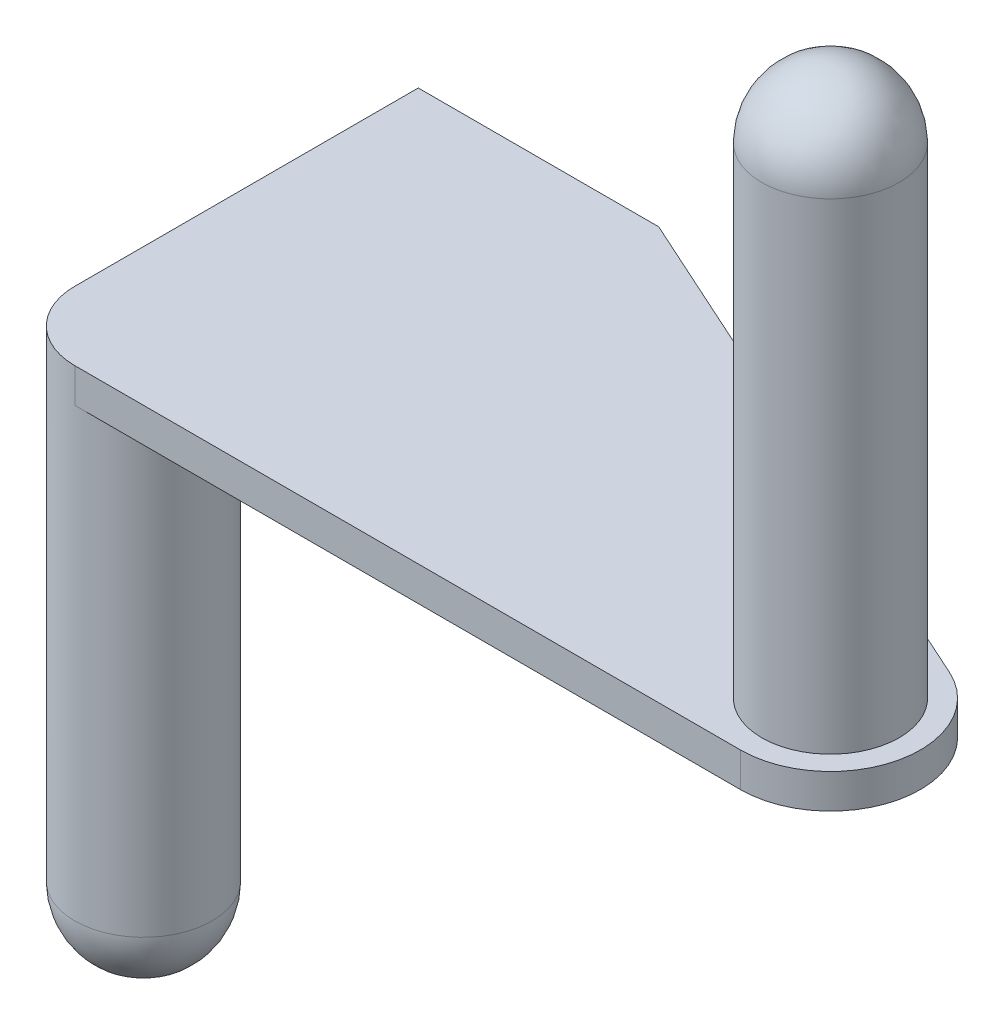
SolidWorks part; units mm, degrees
ref_plane "Front Plane" through (0, 0, 0) normal (0, 0, 1) x (1, 0, 0)
ref_plane "Top Plane" through (0, 0, 0) normal (0, 1, 0) x (1, 0, 0)
ref_plane "Right Plane" through (0, 0, 0) normal (1, 0, 0) x (0, 0, -1)
sketch "Sketch1" plane through (0, 0, 0) normal (0, 1, 0) x (1, 0, 0)
  circle A0 centre (-38.3909, 0) radius 2
extrude "Boss-Extrude1" add sketch "Sketch1" against normal blind 16
fillet "Fillet1" radius 2 1 edges at (-38.3909, -16, 2)
sketch "Sketch2" plane through (0, 0, 0) normal (0, 1, 0) x (1, 0, 0)
  line L0 (-40.3909, 0) -> (-40.3909, 10)
  line L1 (-40.3909, 10) -> (-33.3909, 10)
  line L2 (-33.3909, 10) -> (-17.9286, 3.0008)
  line L3 (-19.0078, -2) -> (-38.3909, -2)
  line L4 (-16.3909, 5.6385) -> (-16.3909, -2.6543) construction
  circle A0 centre (-38.3909, 0) radius 2 construction
  arc A1 (-17.9286, 3.0008) -> (-19.0078, -2) centre (-19.0078, 0.6168) cw
  arc A2 (-38.3909, -2) -> (-40.3909, 0) centre (-38.3909, 0) cw
  dimension "D1" = 7
  dimension "D2" = 24
  dimension "D3" = 12
extrude "Boss-Extrude2" add sketch "Sketch2" against normal blind 1
sketch "Sketch3" plane through (0, 0, 0) normal (0, 1, 0) x (1, 0, 0)
  arc A0 (-19.0078, -2) -> (-17.9286, 3.0008) centre (-19.0078, 0.6168) ccw construction
  arc A1 (-19.0078, -2) -> (-17.9286, 3.0008) centre (-19.0078, 0.6168) ccw
  circle A2 centre (-19.0078, 0.6168) radius 2
extrude "Boss-Extrude3" add sketch "Sketch3" along normal blind 16 contours A2
fillet "Fillet2" radius 2 1 edges at (-19.0078, 16, 1.3832)
sketch "Sketch4" plane through (0, 0, -10) normal (0, 0, -1) x (-1, 0, 0)
  line L0 (33.3909, -1) -> (40.3909, -1) construction
  line L1 (33.3909, -1) -> (40.3909, -1)
  circle A0 centre (36.8909, -4.142) radius 3.5
  point P5 (36.8909, -1)
extrude "Extrude-Thin1" add sketch "Sketch4" against normal blind 3 thin contours L1 A0
fillet "Fillet3" radius 0.2 2 edges at (-38.4329, -1, -8.5) (-35.349, -1, -8.5)
sketch "Sketch5" plane through (0, 0, -10) normal (0, 0, -1) x (-1, 0, 0)
  arc A0 (34.7685, -1.359) -> (39.0134, -1.359) centre (36.8909, -4.142) ccw construction
  arc A1 (34.7685, -1.359) -> (39.0134, -1.359) centre (36.8909, -4.142) ccw
  circle A2 centre (36.8909, -4.142) radius 2
extrude "Cut-Extrude1" cut sketch "Sketch5" against normal blind 6 contours A2
